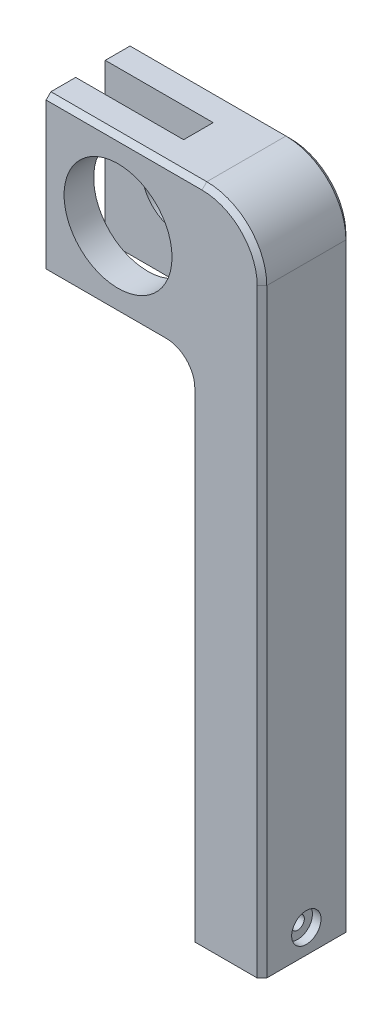
SolidWorks part; units mm, degrees
ref_plane "Front Plane" through (0, 0, 0) normal (0, 0, 1) x (1, 0, 0)
ref_plane "Top Plane" through (0, 0, 0) normal (0, 1, 0) x (1, 0, 0)
ref_plane "Right Plane" through (0, 0, 0) normal (1, 0, 0) x (0, 0, -1)
sketch "Sketch1" plane through (0, 0, 0) normal (0, 0, 1) x (1, 0, 0)
  line L0 (0, 0) -> (-30, 0)
  line L9 (-30, 210) -> (-30, 0)
  line L10 (-30, 210) -> (-90, 210)
  line L11 (-90, 210) -> (-90, 275)
  line L12 (-90, 275) -> (0, 275)
  line L13 (0, 275) -> (0, 0)
  dimension "D1" = 275
  dimension "D2" = 90
  dimension "D3" = 30
  dimension "D4" = 65
extrude "Boss-Extrude1" add sketch "Sketch1" against normal mid plane 37
sketch "Sketch3" plane through (0, 275, 0) normal (0, 1, 0) x (1, 0, 0)
  line L0 (-90, 18.5) -> (-90, -18.5) construction
  line L1 (-45, -6.165) -> (-90, -6.165)
  line L2 (-45, -6.165) -> (-45, 6.165)
  line L3 (-45, 6.165) -> (-90, 6.165)
  line L4 (-90, -6.165) -> (-90, 6.165)
  line L5 (-45, -6.165) -> (-90, 6.165) construction
  line L6 (-45, 6.165) -> (-90, -6.165) construction
  line L7 (-90, 0) -> (0, 0) construction
  point P0 (-67.5, 0)
  dimension "D1" = 12.33
  dimension "D2" = 45
extrude "Cut-Extrude1" cut sketch "Sketch3" against normal up to next
fillet "Fillet1" radius 25 1 edges at (0, 275, 0)
fillet "Fillet2" radius 10 1 edges at (-30, 210, 0)
sketch "Sketch4" plane through (0, 0, 18.5) normal (0, 0, 1) x (1, 0, 0)
  line L0 (-90, 275) -> (-90, 210) construction
  line L1 (-90, 242.5) -> (-39.4804, 242.5) construction
  circle A0 centre (-60, 242.5) radius 22.5
  dimension "D2" = 45
  dimension "D1" = 30
extrude "Cut-Extrude2" cut sketch "Sketch4" against normal up to surface (12.335 mm away) up to face at (-67.5, 242.5, 6.165)
sketch "Sketch5" plane through (0, 0, -18.5) normal (0, 0, -1) x (-1, 0, 0)
  line L0 (90, 242.5) -> (42.6224, 242.5) construction
  line L1 (90, 275) -> (90, 210) construction
  circle A0 centre (60, 242.5) radius 14.625
  dimension "D1" = 30
  dimension "D2" = 29.25
extrude "Cut-Extrude3" cut sketch "Sketch5" against normal up to next
chamfer "Chamfer1" distance 2 angle 45 12 edges at (-65, 210, 18.5) (-32.9289, 207.0711, 18.5) (-30, 100, 18.5) (-65, 210, -18.5) (-32.9289, 207.0711, -18.5) (-30, 100, -18.5) (-57.5, 275, -18.5) (-7.3223, 267.6777, -18.5) (0, 125, -18.5) (-57.5, 275, 18.5) (-7.3223, 267.6777, 18.5) (0, 125, 18.5)
sketch "Sketch9" plane through (0, 0, 0) normal (1, 0, 0) x (0, 0, -1)
  line L0 (0, 0) -> (0, 10) construction
  line L1 (16.5, 0) -> (-16.5, 0) construction
  point P1 (0, 10)
  dimension "D1" = 10
hole_wizard "CBORE for M5 Hex Head Bolt1" positions "Sketch9" profile "Sketch10" counterbore size "M5" standard "ANSI Metric" end condition up to next
sketch "Sketch10" plane through (0, 10, 0) normal (0, 1, 0) x (0, 0, -1)
  line L0 (0, 0) -> (0, 30)
  line L1 (0, 30) -> (2.75, 30)
  line L3 (2.75, 30) -> (2.75, 3.58)
  line L4 (2.75, 3.58) -> (6.12, 3.58)
  line L5 (6.12, 3.58) -> (6.12, 0)
  line L7 (6.12, 0) -> (0, 0)
  line L11 (0, -6.35) -> (0, 107.95) construction
  dimension "Thru Hole Dia." = 5.5
  dimension "Thru Hole Depth" = 30
  dimension "C'Bore Dia." = 12.24
  dimension "C'Bore Depth" = 3.58
sketch "Sketch11" plane through (-90, 0, 0) normal (-1, 0, 0) x (0, 0, 1)
  line L0 (-16.5, 210) -> (-6.165, 210) construction
  line L1 (-12.33, 215) -> (12.33, 215) construction
  line L2 (-12.33, 215) -> (-12.33, 270) construction
  line L3 (-12.33, 270) -> (12.33, 270) construction
  line L4 (12.33, 215) -> (12.33, 270) construction
  line L5 (-12.33, 215) -> (12.33, 270) construction
  line L6 (-12.33, 270) -> (12.33, 215) construction
  line L7 (18.5, 273) -> (18.5, 212) construction
  line L8 (-18.5, 273) -> (-18.5, 212) construction
  point P1 (12.33, 270)
  point P2 (-12.33, 215)
  point P3 (-12.33, 270)
  point P4 (12.33, 215)
  point P20 (0, 0)
  dimension "D1" = 55
  dimension "D2" = 5
  dimension "D3" = 6.17
  dimension "D4" = 6.17
hole_wizard "Ø3.0mm Dowel Hole1" positions "Sketch11" profile "Sketch12" hole size "Ø3.0" standard "ANSI Metric"
sketch "Sketch12" plane through (-90, 270, 12.33) normal (0, 1, 0) x (0, 0, 1)
  line L0 (0, 0) -> (0, 20.9013)
  line L1 (0, 20.9013) -> (1.5, 20)
  line L2 (1.5, 20) -> (1.5, 0)
  line L5 (1.5, 0) -> (0, 0)
  line L10 (0, 20.9013) -> (-1.5, 20) construction
  line L11 (0, -6.35) -> (0, 107.95) construction
  dimension "Hole Dia." = 3
  dimension "Hole Depth" = 20
  dimension "Drill Angle" = 118
